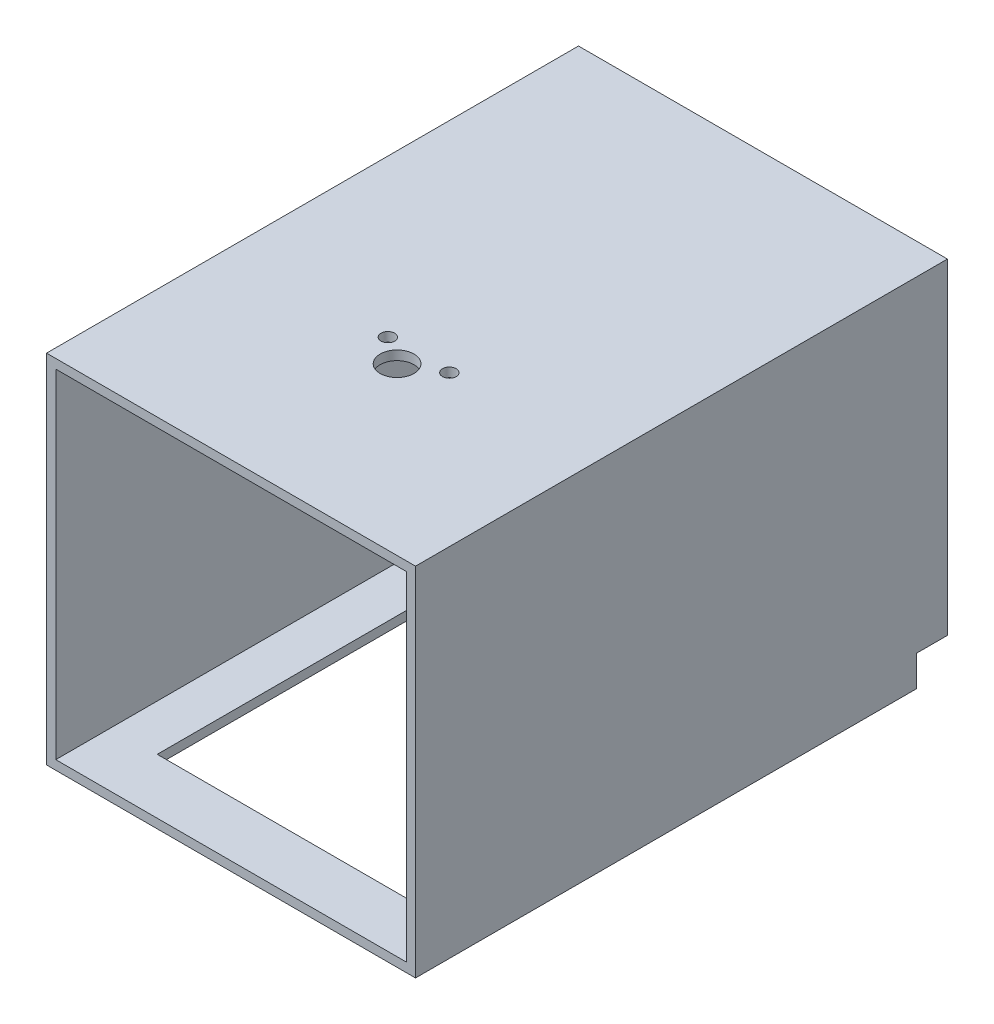
SolidWorks part; units mm, degrees
ref_plane "Front" through (0, 0, 0) normal (0, 0, 1) x (1, 0, 0)
ref_plane "Top" through (0, 0, 0) normal (0, 1, 0) x (1, 0, 0)
ref_plane "Right" through (0, 0, 0) normal (1, 0, 0) x (0, 0, -1)
other "Configuration Table"
sketch "Sketch2" plane through (0, 0, 0) normal (0, 0, 1) x (1, 0, 0)
  line L0 (15, -15) -> (585, -15)
  line L1 (0, 0) -> (600, 0)
  line L2 (0, 0) -> (0, -530)
  line L3 (0, -530) -> (600, -530)
  line L4 (600, 0) -> (600, -530)
  line L5 (585, -15) -> (585, -515)
  line L6 (15, -515) -> (585, -515)
  line L7 (15, -15) -> (15, -515)
  dimension "D1" = 600
  dimension "D2" = 530
  dimension "D3" = 15
extrude "Base-Extrude" add sketch "Sketch2" along normal blind 50
sketch "Sketch3" plane through (0, 0, 50) normal (0, 0, 1) x (1, 0, 0)
  line L0 (600, -530) -> (600, 0) construction
  line L1 (600, 0) -> (0, 0) construction
  line L3 (0, 0) -> (0, -530) construction
  line L4 (600, -580) -> (600, 0)
  line L5 (600, 0) -> (0, 0)
  line L6 (0, -580) -> (600, -580)
  line L7 (0, 0) -> (0, -580)
  line L9 (0, -530) -> (600, -530) construction
  dimension "D1" = 50
extrude "Boss-Extrude2" add sketch "Sketch3" along normal blind 15
sketch "Sketch4" plane through (0, 0, 65) normal (0, 0, 1) x (1, 0, 0)
  line L0 (15, -15) -> (15, -565)
  line L1 (585, -15) -> (15, -15)
  line L2 (585, -565) -> (585, -15)
  line L3 (15, -565) -> (585, -565)
  line L4 (600, 0) -> (0, 0)
  line L5 (0, 0) -> (0, -580)
  line L6 (0, -580) -> (600, -580)
  line L7 (600, -580) -> (600, 0)
  line L8 (600, 0) -> (0, 0)
  line L9 (0, 0) -> (0, -580)
  line L10 (0, -580) -> (600, -580)
  line L11 (600, -580) -> (600, 0)
  dimension "D1" = 0
  dimension "D2" = 15
extrude "Boss-Extrude3" add sketch "Sketch4" along normal blind 800
sketch "Sketch5" plane through (0, -580, 0) normal (0, -1, 0) x (1, 0, 0)
  line L12 (90, 140) -> (510, 140)
  line L13 (510, 140) -> (510, 775)
  line L14 (510, 775) -> (90, 775)
  line L15 (90, 775) -> (90, 140)
  line L16 (90, 140) -> (510, 140)
  line L17 (510, 140) -> (510, 775)
  line L18 (510, 775) -> (90, 775)
  line L19 (90, 775) -> (90, 140)
  dimension "D2" = 635
  dimension "D1" = 90
extrude "Cut-Extrude1" cut sketch "Sketch5" against normal up to next
sketch "Sketch6" plane through (0, -15, 0) normal (0, -1, 0) x (1, 0, 0)
  line L0 (15, 565) -> (585, 565) construction
  line L1 (15, 865) -> (15, 65) construction
  line L2 (300, 575) -> (300, 595) construction
  line L3 (250, 575) -> (350, 575) construction
  line L4 (250, 575) -> (250, 555) construction
  line L5 (250, 555) -> (350, 555) construction
  line L6 (350, 575) -> (350, 555) construction
  line L7 (300, 565) -> (355, 565) construction
  line L8 (585, 865) -> (585, 65) construction
  line L9 (585, 865) -> (585, 65) construction
  line L10 (585, 65) -> (15, 65) construction
  line L11 (0, 865) -> (0, 50) construction
  circle A0 centre (355, 565) radius 11.1803
  circle A1 centre (255, 565) radius 11.1803
  circle A2 centre (300, 595) radius 27.5
  dimension "D6" = 55
  dimension "D5" = 300
  dimension "D2" = 100
  dimension "D3" = 570
  dimension "D4" = 500
  dimension "D7" = 30
extrude "Cut-Extrude2" cut sketch "Sketch6" against normal through all
